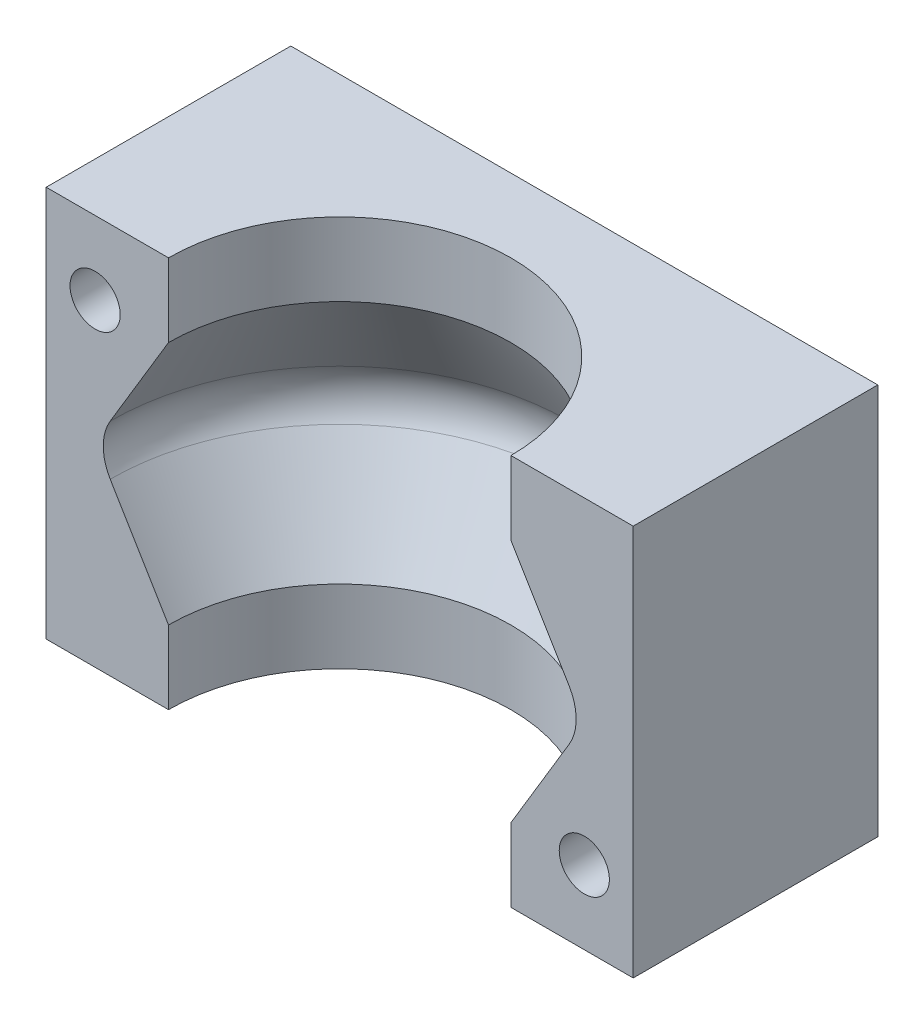
SolidWorks part; units mm, degrees
ref_plane "Front Plane" through (0, 0, 0) normal (0, 0, 1) x (1, 0, 0)
ref_plane "Top Plane" through (0, 0, 0) normal (0, 1, 0) x (1, 0, 0)
ref_plane "Right Plane" through (0, 0, 0) normal (1, 0, 0) x (0, 0, -1)
sketch "Sketch1" plane through (0, 0, 0) normal (0, 0, 1) x (1, 0, 0)
  line L1 (60, -40) -> (-60, -40)
  line L2 (60, -40) -> (60, 40)
  line L3 (60, 40) -> (-60, 40)
  line L4 (-60, -40) -> (-60, 40)
  line L5 (60, -40) -> (-60, 40) construction
  line L6 (60, 40) -> (-60, -40) construction
  point P0 (0, 0)
  dimension "D1" = 120
  dimension "D2" = 80
extrude "Boss-Extrude1" add sketch "Sketch1" along normal blind 50
sketch "Sketch2" plane through (0, 0, 50) normal (0, 0, 1) x (1, 0, 0)
  line L0 (0, 55.4869) -> (0, -55.3328) construction
  line L1 (-67.3036, 0) -> (76.5514, 0) construction
  line L2 (-35, 40) -> (-35, 25)
  line L3 (60, 40) -> (-60, 40) construction
  line L4 (-35, 25) -> (-46.913, 5.145)
  line L5 (-35, -25) -> (-46.913, -5.145)
  line L6 (-35, -40) -> (-35, -25)
  line L7 (-35, 40) -> (0, 40)
  line L9 (0, 40) -> (0, -40)
  line L10 (-60, -40) -> (60, -40) construction
  line L12 (0, -40) -> (-35, -40)
  arc A0 (-46.913, 5.145) -> (-46.913, -5.145) centre (-38.3381, 0) ccw
  point P18 (-50, 0)
  dimension "D4" = 10
  dimension "D1" = 35
  dimension "D2" = 50
  dimension "D3" = 15
sketch "Sketch3" plane through (0, 0, 50) normal (0, 0, 1) x (1, 0, 0)
  line L0 (0, 43.1565) -> (0, -38.2757) construction
  line L1 (-69.1018, 0) -> (69.2302, 0) construction
  circle A3 centre (-50, 25) radius 5.125
  circle A4 centre (50, -25) radius 5.125
  dimension "D1" = 10.25
  dimension "D2" = 50
  dimension "D3" = 25
extrude "Cut-Extrude1" cut sketch "Sketch3" against normal blind 10.2
revolve "Cut-Revolve1" cut sketch "Sketch2" angle 360 about L9
sketch "Sketch4" plane through (0, 0, 0) normal (0, 0, -1) x (-1, 0, 0)
  line L0 (0, 45.8538) -> (0, -47.3951) construction
  line L1 (-71.1568, 0) -> (74.111, 0) construction
  line L2 (-60, 40) -> (60, 40) construction
  circle A0 centre (0, 0) radius 2.5
  circle A1 centre (0, 35) radius 1.5
  circle A2 centre (0, -35) radius 1.5
  dimension "D1" = 5
  dimension "D2" = 3
  dimension "D3" = 5
